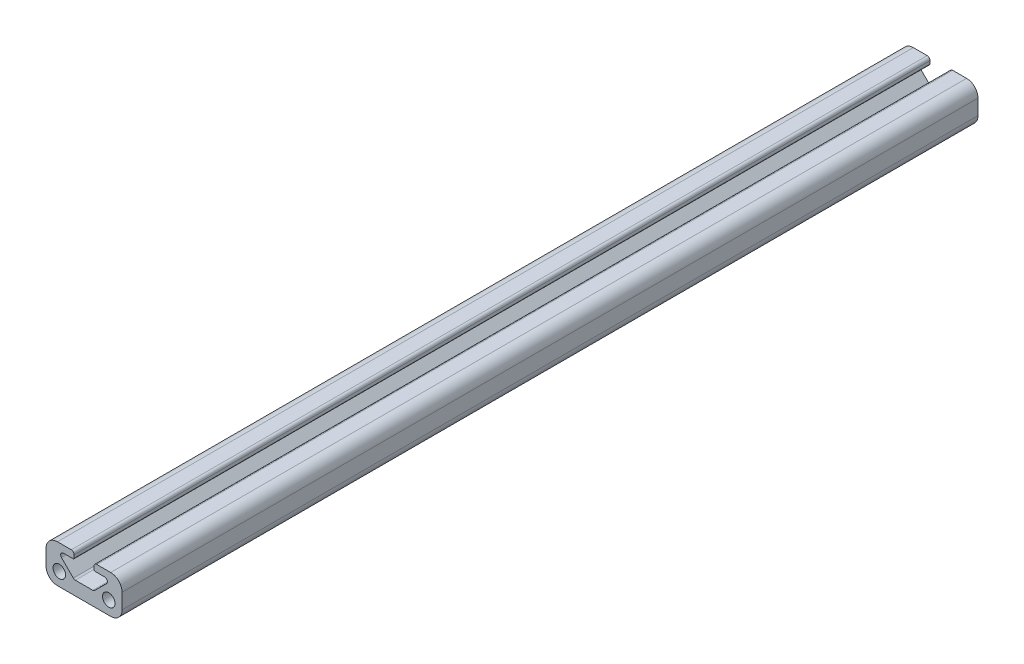
SolidWorks part; units mm, degrees
material "6063-T6"
ref_plane "Front Plane" through (0, 0, 0) normal (0, 0, 1) x (1, 0, 0)
ref_plane "Top Plane" through (0, 0, 0) normal (0, 1, 0) x (1, 0, 0)
ref_plane "Right Plane" through (0, 0, 0) normal (1, 0, 0) x (0, 0, -1)
sketch "Sketch1" plane through (0, 0, 0) normal (0, 0, 1) x (1, 0, 0)
  line L0 (-7, 10) -> (-3.35, 10)
  line L2 (-10, 7) -> (-10, 3)
  line L3 (-7, 0) -> (7, 0)
  line L4 (10, 7) -> (10, 3)
  line L5 (-2.6, 9.25) -> (-2.6, 8.45)
  line L6 (-2.85, 8.2) -> (-5.3893, 8.2)
  line L7 (-5.9197, 6.9197) -> (-2.8197, 3.8197)
  line L8 (-2.2893, 3.6) -> (2.2893, 3.6)
  line L9 (2.8197, 3.8197) -> (5.9197, 6.9197)
  line L10 (5.3893, 8.2) -> (2.85, 8.2)
  line L11 (2.6, 8.45) -> (2.6, 9.25)
  line L12 (3.35, 10) -> (7, 10)
  line L13 (0, -55) -> (0, 55) construction
  line L14 (6.5, 3.5) -> (-6.5, 3.5) construction
  arc A0 (7, 10) -> (10, 7) centre (7, 7) cw
  arc A1 (7, 0) -> (10, 3) centre (7, 3) ccw
  arc A2 (-10, 3) -> (-7, 0) centre (-7, 3) ccw
  arc A3 (-7, 10) -> (-10, 7) centre (-7, 7) ccw
  arc A4 (2.2893, 3.6) -> (2.8197, 3.8197) centre (2.2893, 4.35) ccw
  arc A5 (-2.8197, 3.8197) -> (-2.2893, 3.6) centre (-2.2893, 4.35) ccw
  arc A6 (5.9197, 6.9197) -> (5.3893, 8.2) centre (5.3893, 7.45) ccw
  arc A7 (-5.3893, 8.2) -> (-5.9197, 6.9197) centre (-5.3893, 7.45) ccw
  arc A8 (2.6, 9.25) -> (3.35, 10) centre (3.35, 9.25) cw
  arc A9 (-3.35, 10) -> (-2.6, 9.25) centre (-3.35, 9.25) cw
  arc A10 (2.85, 8.2) -> (2.6, 8.45) centre (2.85, 8.45) cw
  arc A11 (-2.6, 8.45) -> (-2.85, 8.2) centre (-2.85, 8.45) cw
  circle A12 centre (-6.5, 3.5) radius 1.65
  circle A13 centre (6.5, 3.5) radius 1.65
  point P4 (0, 3.6)
  point P18 (0, 3.5)
  point P25 (10, 0)
  point P28 (-10, 0)
  point P31 (-10, 10)
  point P36 (-2.6, 3.6)
  dimension "D6" = 3
  dimension "D7" = 0.75
  dimension "D8" = 0.25
  dimension "D11" = 3.3
  dimension "D1" = 20
  dimension "D2" = 10
  dimension "D3" = 6.4
  dimension "D4" = 5.2
  dimension "D5" = 4.6
  dimension "D9" = 3.5
  dimension "D10" = 13
extrude "Boss-Extrude1" add sketch "Sketch1" along normal mid plane 225
hole_wizard "M5 Clearance Hole1" positions "Sketch2" profile "Sketch3" hole size "M5" standard "ANSI Metric" end condition through all
sketch "Sketch2" plane through (0, 0, 0) normal (0, -1, 0) x (-1, 0, 0)
  line L0 (0, -60) -> (0, 60)
  point P0 (0, 60)
  point P2 (0, -60)
  dimension "D1" = 120
sketch "Sketch3" plane through (0, 0, -60) normal (1, 0, 0) x (0, 0, -1)
  line L0 (0, 0) -> (0, 10)
  line L1 (0, 10) -> (2.6, 10)
  line L2 (2.6, 10) -> (2.6, 0)
  line L5 (2.6, 0) -> (0, 0)
  line L11 (0, -6.35) -> (0, 107.95) construction
  dimension "Thru Hole Dia." = 5.2
  dimension "Thru Hole Depth" = 10
